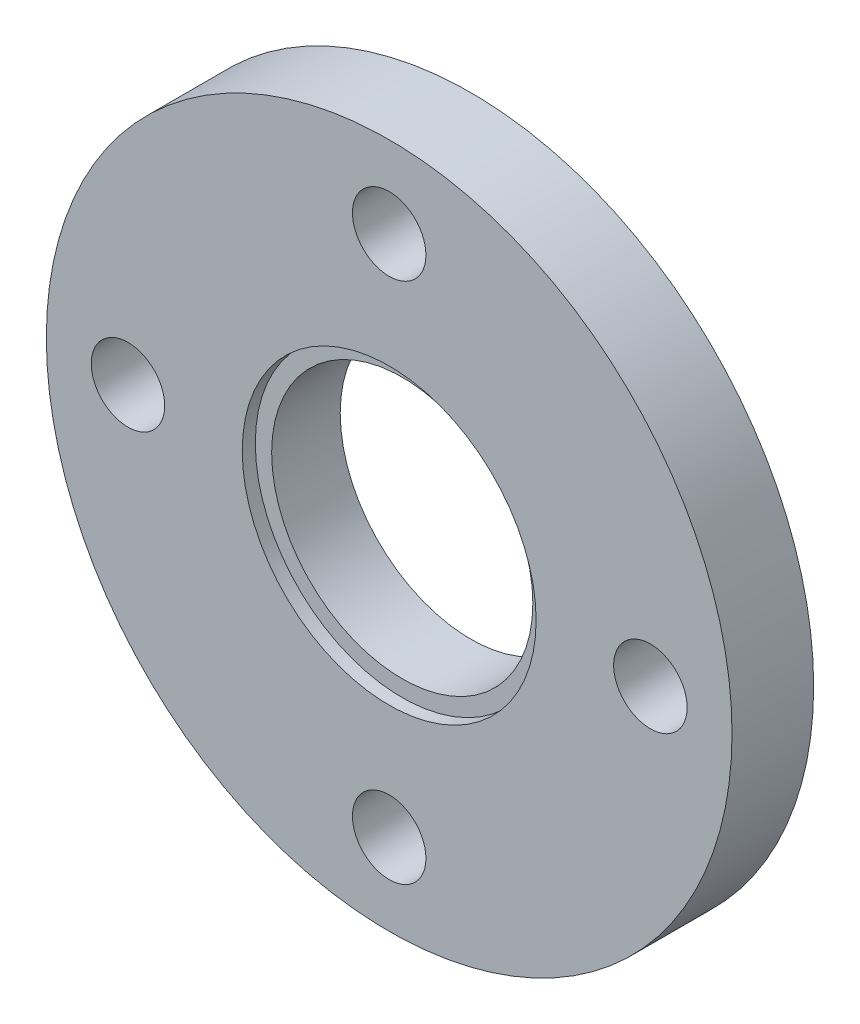
SolidWorks part; units mm, degrees
ref_plane "Спереди" through (0, 0, 0) normal (0, 0, 1) x (1, 0, 0)
ref_plane "Сверху" through (0, 0, 0) normal (0, 1, 0) x (1, 0, 0)
ref_plane "Справа" through (0, 0, 0) normal (1, 0, 0) x (0, 0, -1)
sketch "Эскиз1" plane through (0, 0, 0) normal (0, 0, 1) x (1, 0, 0)
  line L0 (0, 21) -> (0, -21) construction
  line L1 (-21, 0) -> (21, 0) construction
  circle A0 centre (0, 0) radius 21
  circle A1 centre (0, 0) radius 8
  circle A2 centre (0, 0) radius 16 construction
  dimension "D1" = 42
  dimension "D2" = 16
  dimension "D3" = 32
extrude "Бобышка-Вытянуть1" add sketch "Эскиз1" along normal blind 5
hole_wizard "Отверстие с зазором M41" positions "Эскиз3" profile "Эскиз2" hole size "M4" standard "Ansi Metric" end condition through all
sketch "Эскиз3" plane through (0, 0, 5) normal (0, 0, 1) x (1, 0, 0)
  line L0 (0, 21) -> (0, -21) construction
  line L1 (-21, 0) -> (21, 0) construction
  circle A0 centre (0, 0) radius 16 construction
  point P2 (0, 16)
  point P8 (-16, 0)
  point P12 (0, -16)
  point P14 (16, 0)
sketch "Эскиз2" plane through (0, 16, 5) normal (1, 0, 0) x (0, -1, 0)
  line L0 (0, 0) -> (0, 5)
  line L1 (0, 5) -> (2.25, 5)
  line L2 (2.25, 5) -> (2.25, 0)
  line L5 (2.25, 0) -> (0, 0)
  line L11 (0, -6.35) -> (0, 107.95) construction
  dimension "Диаметр сквозного отверстия" = 4.5
  dimension "Глубина сквозного отверстия" = 5
sketch "Эскиз4" plane through (0, 0, 5) normal (0, 0, 1) x (1, 0, 0)
  circle A0 centre (0, 0) radius 9
  dimension "D1" = 18
extrude "Вырез-Вытянуть1" cut sketch "Эскиз4" against normal blind 0.8
